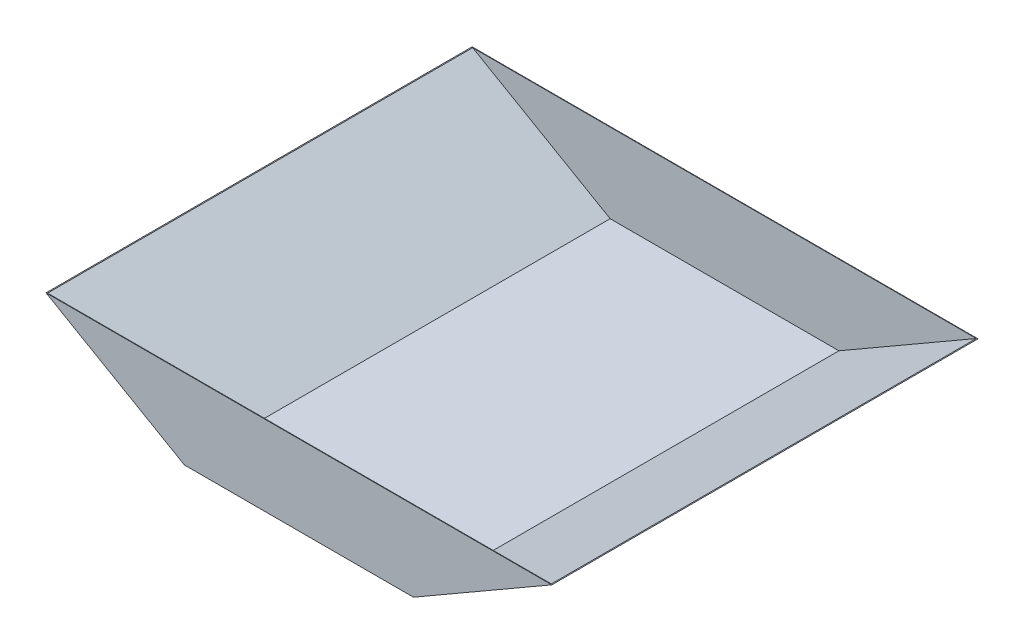
SolidWorks part; units mm, degrees
material "Epoxy, Unfilled"
ref_plane "Front Plane" through (0, 0, 0) normal (0, 0, 1) x (1, 0, 0)
ref_plane "Top Plane" through (0, 0, 0) normal (0, 1, 0) x (1, 0, 0)
ref_plane "Right Plane" through (0, 0, 0) normal (1, 0, 0) x (0, 0, -1)
sketch "Sketch1" plane through (0, 0, 0) normal (0, 0, 1) x (1, 0, 0)
  line L0 (-978.3154, 0) -> (-548.3154, 0)
  line L1 (-548.3154, 0) -> (-288.5078, 150)
  line L2 (-288.5078, 150) -> (-1238.123, 150)
  line L3 (-1238.123, 150) -> (-978.3154, 0)
  point P4 (0, 0)
  point P6 (0, 0)
  dimension "D1" = 430
  dimension "D2" = 300
  dimension "D3" = 300
  dimension "D4" = 150
extrude "Boss-Extrude1" add sketch "Sketch1" along normal blind 800
shell "Shell1" thickness 1
